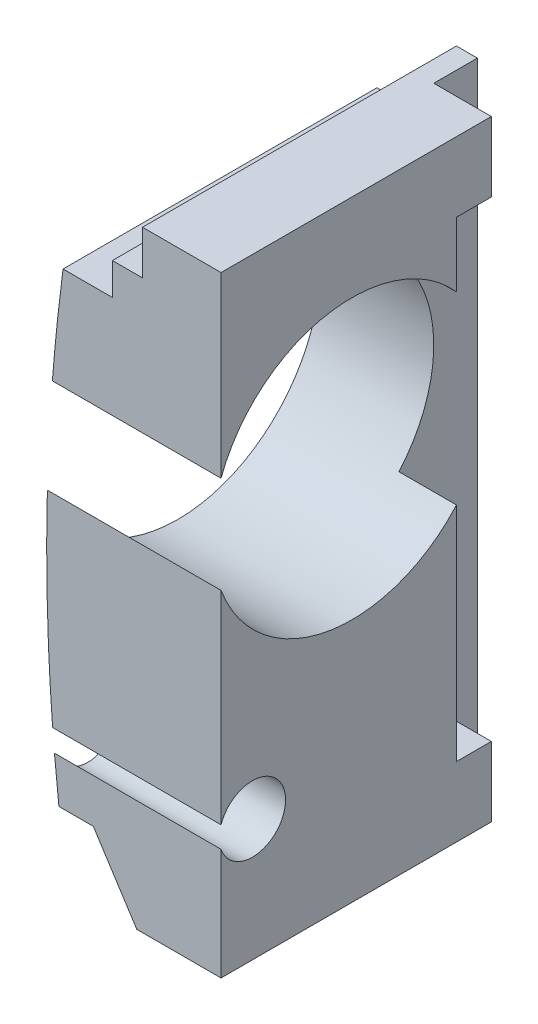
SolidWorks part; units mm, degrees
ref_plane "Front" through (0, 0, 0) normal (0, 0, 1) x (1, 0, 0)
ref_plane "Top" through (0, 0, 0) normal (0, 1, 0) x (1, 0, 0)
ref_plane "Right" through (0, 0, 0) normal (1, 0, 0) x (0, 0, -1)
sketch "Çizim1" plane through (0, 0, 0) normal (0, 0, 1) x (1, 0, 0)
  line L0 (-29.5727, 30.8982) -> (-27.8454, 30.8982) construction
  line L1 (-27.9474, -2.6188) -> (-22.3424, -2.6188) construction
  line L2 (-30.4401, 1.2509) -> (-27.9474, -2.6188) construction
  line L3 (-27.8454, 30.8982) -> (-27.8454, 33.416) construction
  line L4 (-22.3424, 33.416) -> (-27.8454, 33.416) construction
  line L5 (-29.5727, 30.8982) -> (-29.5727, 29.0626) construction
  line L6 (-29.5727, 29.0626) -> (-32.3414, 29.0626) construction
  line L7 (-32.5854, 1.2509) -> (-30.4401, 1.2509) construction
  line L8 (-29.0727, 30.3982) -> (-27.3454, 30.3982)
  line L9 (-27.3454, 30.3982) -> (-27.3454, 32.916)
  line L10 (-22.8424, 32.916) -> (-27.3454, 32.916)
  line L11 (-22.8424, 32.916) -> (-22.8424, -2.1188)
  line L12 (-22.3424, 33.416) -> (-22.3424, -2.6188) construction
  line L13 (-27.6748, -2.1188) -> (-22.8424, -2.1188)
  line L14 (-30.1674, 1.7509) -> (-27.6748, -2.1188)
  line L15 (-32.1398, 1.7509) -> (-30.1674, 1.7509)
  line L16 (-29.0727, 28.5626) -> (-31.9036, 28.5626)
  line L17 (-29.0727, 30.3982) -> (-29.0727, 28.5626)
  spline S0 degree 1 poles (-31.9036, 28.5626) (-32.1398, 1.7509) knots 0 0 1 1 construction
  spline S1 degree 3 poles (-32.1398, 1.7509) (-32.4952, 4.8859) (-32.8647, 10.1522) (-32.8494, 19.1241) (-32.3823, 24.9148) (-31.9036, 28.5626) knots 0.015717 0.015717 0.015717 0.015717 0.357537 0.585418 0.984004 0.984004 0.984004 0.984004
  spline S4 degree 2 poles (-32.3414, 29.0626) (-33.277, 22.1452) (-33.3383, 15.1644) (-33.3995, 8.1842) (-32.5854, 1.2509) knots 0 0 0 0.5 0.5 1 1 1 construction
  point P0 (-32.8424, 14.3752)
  dimension "D2" = 10
  dimension "D1" = 0.5
extrude "Yükseklik-Ekstrüzyon1" add sketch "Çizim1" along normal blind 18
sketch "Çizim2" plane through (0, -2.1188, 0) normal (0, -1, 0) x (-1, 0, 0)
  line L0 (22.8424, 0) -> (27.3454, 0) construction
  line L1 (21.2113, 0) -> (26.1441, 0)
  line L2 (21.2113, 0) -> (21.2113, -2.5)
  line L3 (21.2113, -2.5) -> (26.1441, -2.5)
  line L4 (26.1441, 0) -> (26.1441, -2.5)
  dimension "D1" = 0
  dimension "D2" = 2.5
extrude "Kes-Ekstrüzyon1" cut sketch "Çizim2" against normal blind 50
sketch "Çizim3" plane through (-22.8424, 0, 0) normal (1, 0, 0) x (0, 0, -1)
  line L0 (0, -2.1188) -> (0, 32.916) construction
  line L1 (-18, -2.1188) -> (-2.5, -2.1188) construction
  circle A0 centre (-16.2, 4.8812) radius 1.9
  dimension "D1" = 3.8
  dimension "D2" = 16.2
  dimension "D3" = 7
extrude "Kes-Ekstrüzyon2" cut sketch "Çizim3" against normal blind 50
sketch "Çizim5" plane through (-22.8424, 0, 0) normal (1, 0, 0) x (0, 0, -1)
  line L0 (-2.5, -2.1188) -> (-2.5, 32.916) construction
  line L1 (-2.5, 1.8812) -> (-4.5, 1.8812)
  line L2 (-2.5, 1.8812) -> (-2.5, 28.916)
  line L3 (-2.5, 28.916) -> (-4.5, 28.916)
  line L4 (-4.5, 1.8812) -> (-4.5, 28.916)
  line L5 (-18, -2.1188) -> (-2.5, -2.1188) construction
  line L6 (-18, 32.916) -> (-2.5, 32.916) construction
  dimension "D1" = 2
  dimension "D2" = 4
  dimension "D3" = 4
extrude "Kes-Ekstrüzyon6" cut sketch "Çizim5" against normal up to surface (3.3017 mm away) up to face at (-26.1441, 15.3986, 1.25)
sketch "Çizim4" plane through (-22.8424, 0, 0) normal (1, 0, 0) x (0, 0, -1)
  line L0 (-18, 32.916) -> (-2.5, 32.916) construction
  line L1 (-2.5, -2.1188) -> (-2.5, 1.8812) construction
  circle A0 centre (-10.5, 19.916) radius 8
  dimension "D2" = 16
  dimension "D1" = 13
  dimension "D3" = 8
extrude "Kes-Ekstrüzyon5" cut sketch "Çizim4" against normal blind 50
